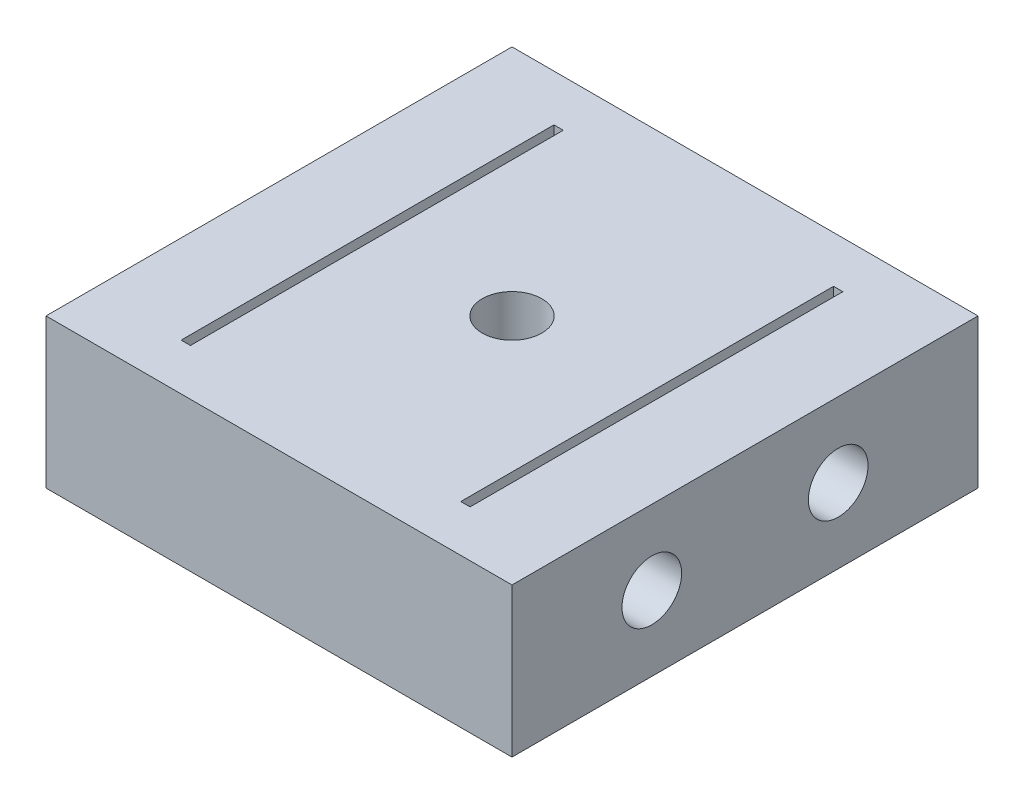
SolidWorks part; units mm, degrees
ref_plane "Front Plane" through (0, 0, 0) normal (0, 0, 1) x (1, 0, 0)
ref_plane "Top Plane" through (0, 0, 0) normal (0, 1, 0) x (1, 0, 0)
ref_plane "Right Plane" through (0, 0, 0) normal (1, 0, 0) x (0, 0, -1)
sketch "Sketch2" plane through (0, 0, 0) normal (0, 1, 0) x (1, 0, 0)
  line L0 (12.5, 0) -> (12.5, 25) construction
  line L1 (0, 0) -> (25, 0)
  line L2 (0, 0) -> (0, 25)
  line L3 (0, 25) -> (25, 25)
  line L4 (25, 0) -> (25, 25)
  line L5 (4.75, 22.5) -> (5.25, 22.5)
  line L6 (4.75, 22.5) -> (4.75, 2.5)
  line L7 (4.75, 2.5) -> (5.25, 2.5)
  line L8 (5.25, 22.5) -> (5.25, 2.5)
  line L9 (19.75, 22.5) -> (20.25, 22.5)
  line L10 (19.75, 22.5) -> (19.75, 2.5)
  line L11 (19.75, 2.5) -> (20.25, 2.5)
  line L12 (20.25, 22.5) -> (20.25, 2.5)
  line L13 (5, 22.5) -> (5, 2.5) construction
  line L14 (20, 2.5) -> (20, 22.5) construction
  circle A0 centre (12.5, 12.5) radius 1.6
  point P19 (12.5, 12.5)
  point P20 (5.25, 12.5)
  point P21 (19.75, 12.5)
  dimension "D1" = 3.2
  dimension "D2" = 25
  dimension "D3" = 25
  dimension "D4" = 0.5
  dimension "D5" = 15
  dimension "D6" = 20
extrude "Boss-Extrude1" add sketch "Sketch2" along normal blind 8
sketch "Sketch3" plane through (25, 0, 0) normal (1, 0, 0) x (0, 0, -1)
  line L0 (25, 8) -> (25, 0) construction
  line L1 (0, 0) -> (25, 0) construction
  circle A0 centre (7.5, 4) radius 1.6
  circle A1 centre (17.5, 4) radius 1.6
  point P6 (25, 4)
  point P9 (12.5, 0)
  dimension "D3" = 3.2
  dimension "D1" = 5
  dimension "D2" = 5
extrude "Cut-Extrude1" cut sketch "Sketch3" against normal through all
